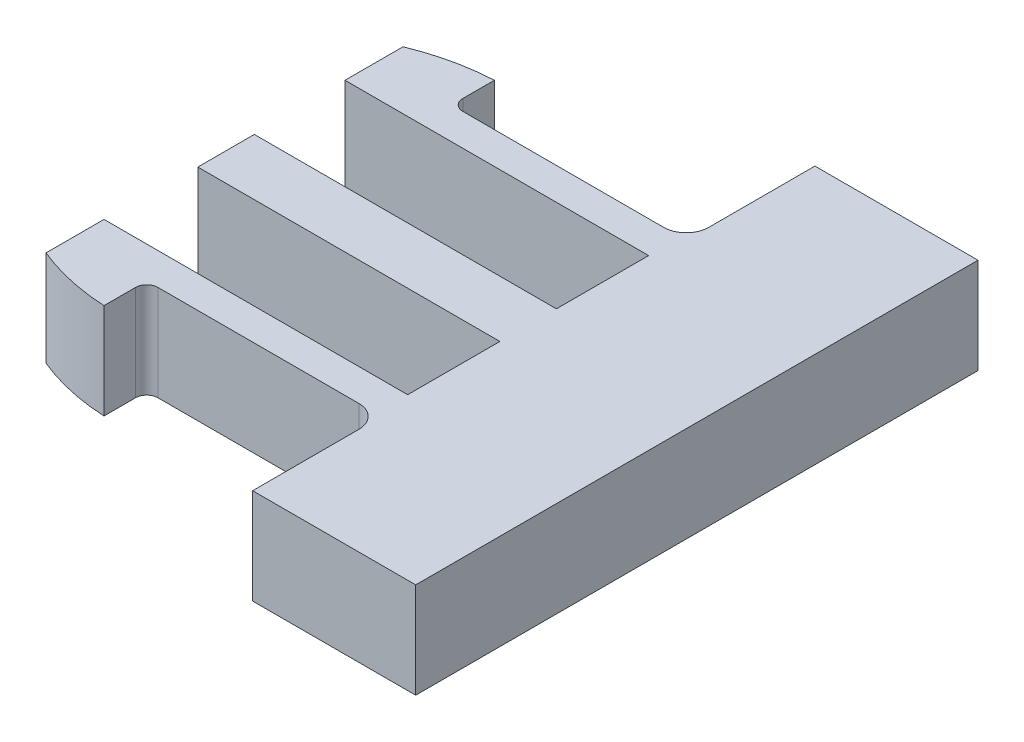
SolidWorks part; units mm, degrees
ref_plane "Alzado" through (0, 0, 0) normal (0, 0, 1) x (1, 0, 0)
ref_plane "Planta" through (0, 0, 0) normal (0, 1, 0) x (1, 0, 0)
ref_plane "Vista lateral" through (0, 0, 0) normal (1, 0, 0) x (0, 0, -1)
sketch "Croquis1" plane through (0, 0, 0) normal (0, 1, 0) x (1, 0, 0)
  line L0 (13.2702, -24.7145) -> (13.2702, -14.7145)
  line L1 (13.2702, 24.7145) -> (13.2702, 14.7145)
  line L2 (13.2702, 24.7145) -> (28.2702, 24.7145)
  line L3 (28.2702, 24.7145) -> (28.2702, -24.7145)
  line L5 (13.2702, -24.7145) -> (28.2702, -24.7145)
  line L6 (13.2702, -14.7145) -> (28.2702, -14.7145) construction
  line L7 (-6.9906, 14.7145) -> (28.2702, 14.7145) construction
  line L8 (-7.0906, 15.2145) -> (-7.0906, 18.9955)
  line L11 (28.2702, 0) -> (-28.1565, 0) construction
  line L12 (-6.5906, 14.7145) -> (13.2702, 14.7145)
  line L13 (-16.0906, 14.7145) -> (-16.0906, 10.7145)
  line L14 (-16.0906, 10.7145) -> (13.2702, 10.7145)
  line L15 (13.2702, 10.7145) -> (13.2702, 8.2145)
  line L17 (-16.0906, 3.0122) -> (-16.0906, -3.0122)
  line L20 (-16.0906, -10.7145) -> (13.2702, -10.7145)
  line L21 (-16.0906, -14.7145) -> (-16.0906, -10.7145)
  line L23 (-7.0906, -18.9955) -> (-7.0906, -14.7145)
  line L24 (13.2702, -14.7145) -> (-7.0906, -14.7145)
  line L25 (13.2702, 8.2145) -> (13.2702, 5.2122)
  line L29 (13.2702, 5.2122) -> (13.2702, 5.0122)
  line L35 (-16.0906, 10.7145) -> (-16.0906, 5.2145) construction
  line L36 (-16.0906, 3.0122) -> (13.2702, 3.0122)
  line L37 (13.2702, 3.0122) -> (13.2702, 5.0122)
  line L38 (13.2702, -10.7145) -> (13.2702, -8.2145)
  line L39 (13.2702, -3.0122) -> (13.2702, -5.0122)
  line L40 (-16.0906, -3.0122) -> (13.2702, -3.0122)
  line L41 (13.2702, -5.2122) -> (13.2702, -5.0122)
  line L42 (13.2702, -8.2145) -> (13.2702, -5.2122)
  arc A0 (-7.0906, 18.9955) -> (-8.0906, 19.9955) centre (-8.0906, 18.9955) ccw
  arc A2 (-6.5906, 14.7145) -> (-7.0906, 15.2145) centre (-6.5906, 15.2145) cw
  arc A4 (-7.0906, -18.9955) -> (-8.0906, -19.9955) centre (-8.0906, -18.9955) cw
  arc A5 (-16.0906, -14.7145) -> (-8.0906, -19.9955) centre (-6.7369, -9.2447) ccw
  arc A6 (-16.0906, 14.7145) -> (-8.0906, 19.9955) centre (-6.7369, 9.2447) cw
  point P30 (-16.0906, 0)
  point P39 (-16.0906, 0)
  point P48 (-16.0906, 0)
  dimension "D2" = 1
  dimension "D3" = 10.8356
  dimension "D4" = 0.5
  dimension "D1" = 10
  dimension "D5" = 4
  dimension "D6" = 2.5
  dimension "D7" = 15
  dimension "D8" = 49.429
  dimension "D9" = 5.5
  dimension "0.2" = 0.2
  dimension "D10" = 29.3608
extrude "Saliente-Extruir1" add sketch "Croquis1" along normal blind 8.5
fillet "Redondeo1" radius 2 2 edges at (13.2702, 4.25, 14.7145) (13.2702, 4.25, -14.7145)
sketch "Croquis2" plane through (0, 8.5, 0) normal (0, 1, 0) x (1, 0, 0)
  line L0 (-7.0906, 14.7145) -> (-7.0906, 19.9955) construction
  line L1 (-7.0906, 17.355) -> (-16.0906, 14.7145) construction
  line L2 (-16.0906, 14.7145) -> (-7.0906, 14.7145) construction
  line L3 (-7.0906, 18.9955) -> (-7.0906, 17.355)
  line L4 (-16.0906, 0) -> (28.2702, 0) construction
  line L5 (-16.0906, 3.0122) -> (-16.0906, -3.0122) construction
  line L6 (28.2702, 24.7145) -> (28.2702, -24.7145) construction
  line L7 (-7.0906, -18.9955) -> (-7.0906, -17.355)
  arc A0 (-16.0906, 14.7145) -> (-7.0906, 17.355) centre (-6.1172, -2.6213) cw
  arc A1 (-16.0906, 14.7145) -> (-8.0906, 19.9955) centre (-6.7369, 9.2447) cw
  arc A2 (-8.0906, 19.9955) -> (-7.0906, 18.9955) centre (-8.0906, 18.9955) cw
  arc A3 (-8.0906, -19.9955) -> (-7.0906, -18.9955) centre (-8.0906, -18.9955) ccw
  arc A4 (-16.0906, -14.7145) -> (-8.0906, -19.9955) centre (-6.7369, -9.2447) ccw
  arc A5 (-16.0906, -14.7145) -> (-7.0906, -17.355) centre (-6.1172, 2.6213) ccw
  dimension "D1" = 20
extrude "Cortar-Extruir1" cut sketch "Croquis2" against normal blind 10
sketch "Croquis3" plane through (0, 8.5, 0) normal (0, 1, 0) x (1, 0, 0)
  line L1 (-16.0906, 17.982) -> (-14.0906, 17.982)
  line L2 (-14.0906, 17.982) -> (-14.0906, -19.659)
  line L3 (-14.0906, -19.659) -> (-16.0906, -19.659)
  line L4 (-16.0906, -19.659) -> (-16.0906, 17.982)
  dimension "D1" = 2
extrude "Cortar-Extruir2" cut sketch "Croquis3" against normal blind 10
sketch "Croquis4" plane through (0, 8.5, 0) normal (0, 1, 0) x (1, 0, 0)
  line L0 (13.2702, 24.7145) -> (13.2702, 16.7145) construction
  line L1 (-7.0906, 17.355) -> (13.2702, 17.355)
  line L2 (-7.0906, 17.355) -> (-7.0906, 13.555)
  line L3 (-7.0906, 13.555) -> (13.2702, 13.555)
  line L4 (13.2702, 17.355) -> (13.2702, 13.555)
  line L5 (-14.0906, 0) -> (17.2653, 0) construction
  line L6 (-14.0906, -3.0122) -> (-14.0906, 3.0122) construction
  line L7 (-7.0906, -13.555) -> (13.2702, -13.555)
  line L8 (13.2702, -17.355) -> (13.2702, -13.555)
  line L9 (-7.0906, -17.355) -> (13.2702, -17.355)
  line L10 (-7.0906, -17.355) -> (-7.0906, -13.555)
  dimension "D1" = 3.8
extrude "Cortar-Extruir3" cut sketch "Croquis4" against normal blind 10
fillet "Redondeo2" radius 1 2 edges at (-7.0906, 4.25, -13.555) (-7.0906, 4.25, 13.555)
fillet "Redondeo3" radius 2 2 edges at (13.2702, 4.25, -13.555) (13.2702, 4.25, 13.555)
sketch "Croquis6" plane through (0, 8.5, 0) normal (0, 1, 0) x (1, 0, 0)
  line L0 (-14.0906, -3.0122) -> (13.2702, -3.0122) construction
  line L1 (-14.0906, -3.0122) -> (-14.0906, 3.0122) construction
  line L2 (-14.0906, 3.0122) -> (13.2702, 3.0122) construction
  line L3 (-14.0906, -3.0122) -> (13.2702, -3.0122)
  line L4 (-14.0906, -3.0122) -> (-14.0906, 3.0122)
  line L5 (-14.0906, 3.0122) -> (13.2702, 3.0122)
  line L6 (-13.5906, -2.5122) -> (13.2702, -2.5122)
  line L7 (-13.5906, -2.5122) -> (-13.5906, 2.5122)
  line L8 (-13.5906, 2.5122) -> (13.2702, 2.5122)
  line L9 (13.2702, 3.0122) -> (13.2702, 2.5122)
  line L10 (13.2702, -2.5122) -> (13.2702, -3.0122)
  dimension "D1" = 0.5
extrude "Cortar-Extruir4" cut sketch "Croquis6" against normal blind 10
sketch "Croquis7" plane through (0, 8.5, 0) normal (0, 1, 0) x (1, 0, 0)
  line L0 (-6.0906, 13.555) -> (11.2702, 13.555) construction
  line L1 (13.2702, 24.7145) -> (13.7702, 24.7145)
  line L3 (13.2702, 13.555) -> (13.7702, 13.555)
  line L5 (-13.5906, 0) -> (-11.5817, 0) construction
  line L6 (-13.5906, -2.5122) -> (-13.5906, 2.5122) construction
  line L11 (13.2702, 24.7145) -> (10.8505, 24.7145)
  line L12 (10.8505, 24.7145) -> (10.8505, 13.555)
  line L13 (10.8505, 13.555) -> (13.2702, 13.555)
  line L14 (13.2702, -24.7145) -> (10.8505, -24.7145)
  line L15 (10.8505, -24.7145) -> (10.8505, -13.555)
  line L16 (10.8505, -13.555) -> (13.2702, -13.555)
  line L17 (13.2702, -13.555) -> (13.7702, -13.555)
  line L19 (13.2702, -24.7145) -> (13.7702, -24.7145)
  line L20 (13.7702, 24.7145) -> (13.7702, 13.555)
  line L21 (13.7702, -13.555) -> (13.7702, -24.7145)
extrude "Cortar-Extruir5" cut sketch "Croquis7" against normal blind 10
fillet "Redondeo4" radius 2 2 edges at (13.7702, 4.25, 13.555) (13.7702, 4.25, -13.555)
sketch "Croquis8" plane through (0, 8.5, 0) normal (0, 1, 0) x (1, 0, 0)
  line L0 (28.2702, 0) -> (-13.7298, 0) construction
  line L1 (28.2702, 25) -> (28.2702, -25) construction
  line L2 (28.2702, -25) -> (-13.7298, -25) construction
  line L3 (-13.7298, -25) -> (-13.7298, 25) construction
  line L5 (28.2702, 24.7145) -> (28.2702, -24.7145) construction
  line L6 (-13.7298, 0) -> (-13.7298, 25) construction
  line L7 (-13.7298, 25) -> (28.2702, 25) construction
  dimension "D1" = 42
  dimension "D2" = 25
  dimension "D3" = 50
sketch "Croquis9" plane through (0, 8.5, 0) normal (0, 1, 0) x (1, 0, 0)
  line L0 (-14.0906, -15.7206) -> (-14.0906, -10.7145) construction
  line L1 (-13.7298, 25) -> (-14.0906, 25)
  line L2 (-13.7298, 25) -> (-13.7298, -16.6773)
  line L3 (-13.7298, -16.6773) -> (-14.0906, -16.6773)
  line L4 (-14.0906, 25) -> (-14.0906, -16.6773)
extrude "Cortar-Extruir6" cut sketch "Croquis9" against normal blind 10
sketch "Croquis10" plane through (0, 8.5, 0) normal (0, 1, 0) x (1, 0, 0)
  line L0 (-13.7298, 25) -> (28.2702, 25) construction
  line L1 (13.7702, 25) -> (28.2702, 25)
  line L2 (13.7702, 25) -> (13.7702, 24.7145)
  line L3 (13.7702, 24.7145) -> (28.2702, 24.7145)
  line L4 (28.2702, 25) -> (28.2702, 24.7145)
  line L5 (13.7702, 15.555) -> (13.7702, 24.7145) construction
  line L6 (28.2702, 0) -> (-1.5399, 0) construction
  line L7 (28.2702, 25) -> (28.2702, -25) construction
  line L8 (28.2702, 0) -> (-13.7298, 0) construction
  line L9 (28.2702, -25) -> (28.2702, -24.7145)
  line L10 (13.7702, -24.7145) -> (28.2702, -24.7145)
  line L11 (13.7702, -25) -> (13.7702, -24.7145)
  line L12 (13.7702, -25) -> (28.2702, -25)
extrude "Saliente-Extruir2" add sketch "Croquis10" against normal blind 8.5
